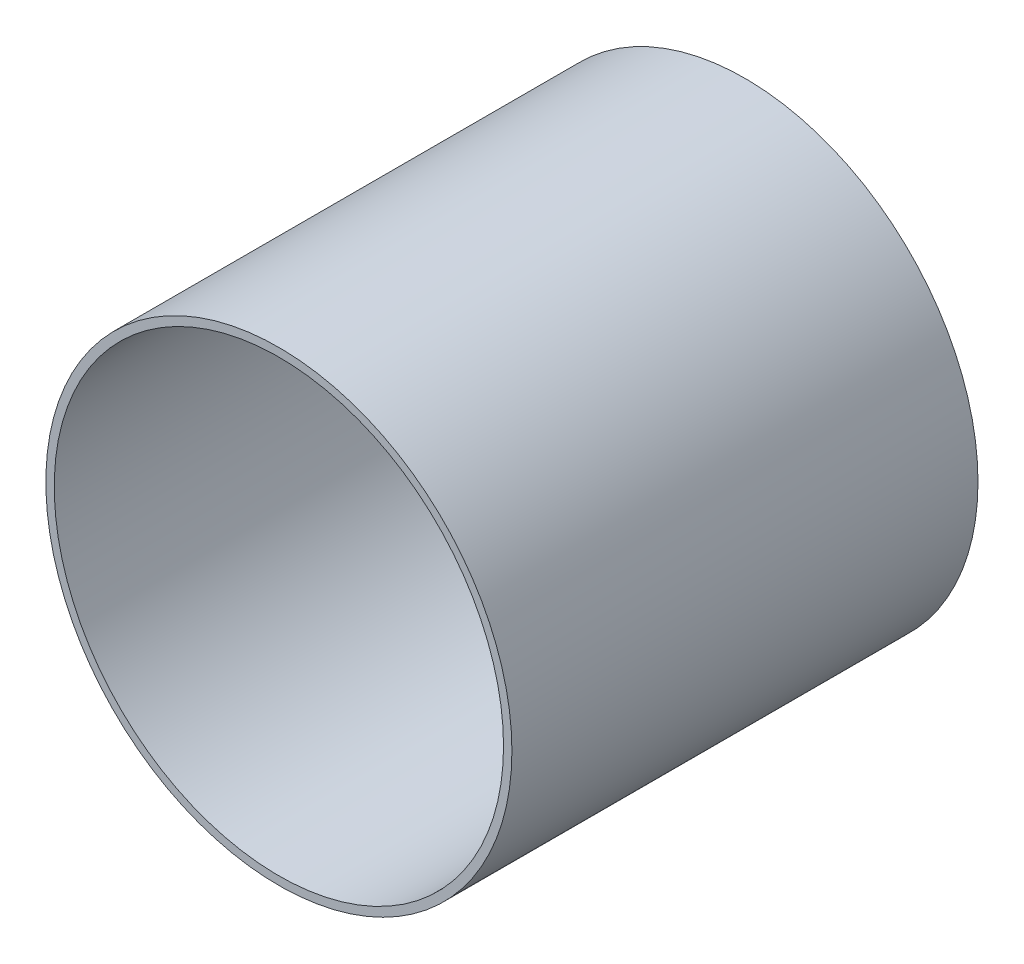
SolidWorks part; units mm, degrees
ref_plane "Front Plane" through (0, 0, 0) normal (0, 0, 1) x (1, 0, 0)
ref_plane "Top Plane" through (0, 0, 0) normal (0, 1, 0) x (1, 0, 0)
ref_plane "Right Plane" through (0, 0, 0) normal (1, 0, 0) x (0, 0, -1)
sketch "Sketch1" plane through (0, 0, 0) normal (0, 0, 1) x (1, 0, 0)
  circle A0 centre (0, 0) radius 12.05
  circle A1 centre (0, 0) radius 12.5
  dimension "D1" = 25
  dimension "D2" = 24.1
extrude "Boss-Extrude1" add sketch "Sketch1" along normal blind 25
